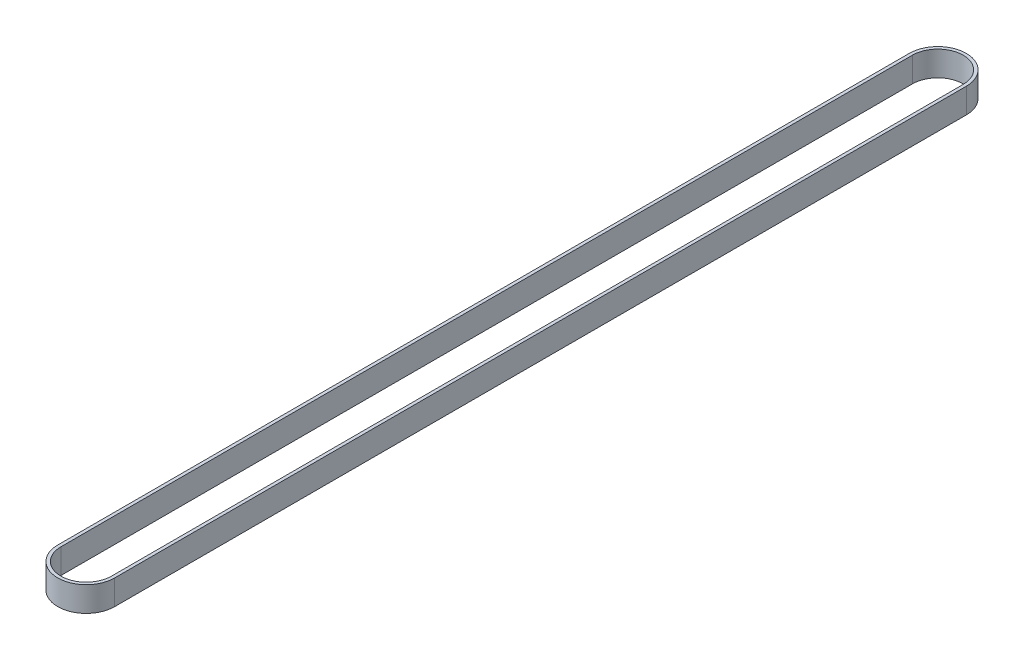
SolidWorks part; units mm, degrees
material "天然橡胶"
ref_plane "前视基准面" through (0, 0, 0) normal (0, 0, 1) x (1, 0, 0)
ref_plane "上视基准面" through (0, 0, 0) normal (0, 1, 0) x (1, 0, 0)
ref_plane "右视基准面" through (0, 0, 0) normal (1, 0, 0) x (0, 0, -1)
other "Configuration Table"
sketch "草图1" plane through (0, 0, 0) normal (0, 1, 0) x (1, 0, 0)
  line L0 (0, -102.55) -> (0, 102.55) construction
  line L1 (-6.86, -102.55) -> (-6.86, 102.55)
  line L2 (6.86, -102.55) -> (6.86, 102.55)
  line L3 (0, -102.55) -> (0, 102.55) construction
  line L4 (-6.11, -102.55) -> (-6.11, 102.55)
  line L5 (6.11, -102.55) -> (6.11, 102.55)
  arc A0 (-6.86, -102.55) -> (6.86, -102.55) centre (0, -102.55) ccw
  arc A1 (6.86, 102.55) -> (-6.86, 102.55) centre (0, 102.55) ccw
  arc A2 (-6.11, -102.55) -> (6.11, -102.55) centre (0, -102.55) ccw
  arc A3 (6.11, 102.55) -> (-6.11, 102.55) centre (0, 102.55) ccw
  point P2 (0, 0)
  point P9 (0, 0)
  dimension "D3" = 6.11
  dimension "D4" = 6.86
  dimension "D1" = 205.1
  dimension "D2" = 205.1
extrude "凸台-拉伸1" add sketch "草图1" along normal blind 6
